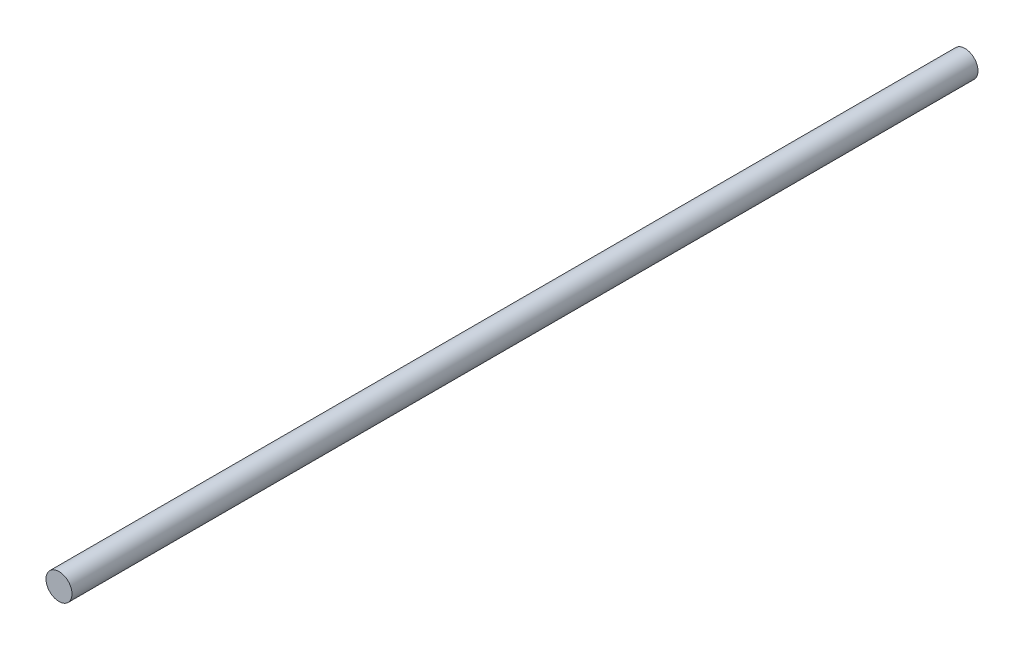
SolidWorks part; units mm, degrees
ref_plane "Front Plane" through (0, 0, 0) normal (0, 0, 1) x (1, 0, 0)
ref_plane "Top Plane" through (0, 0, 0) normal (0, 1, 0) x (1, 0, 0)
ref_plane "Right Plane" through (0, 0, 0) normal (1, 0, 0) x (0, 0, -1)
sketch "Sketch1" plane through (0, 0, 0) normal (0, 0, 1) x (1, 0, 0)
  circle A0 centre (0, 0) radius 3.175
  dimension "D1" = 6.35
extrude "Boss-Extrude1" add sketch "Sketch1" along normal blind 220.98
